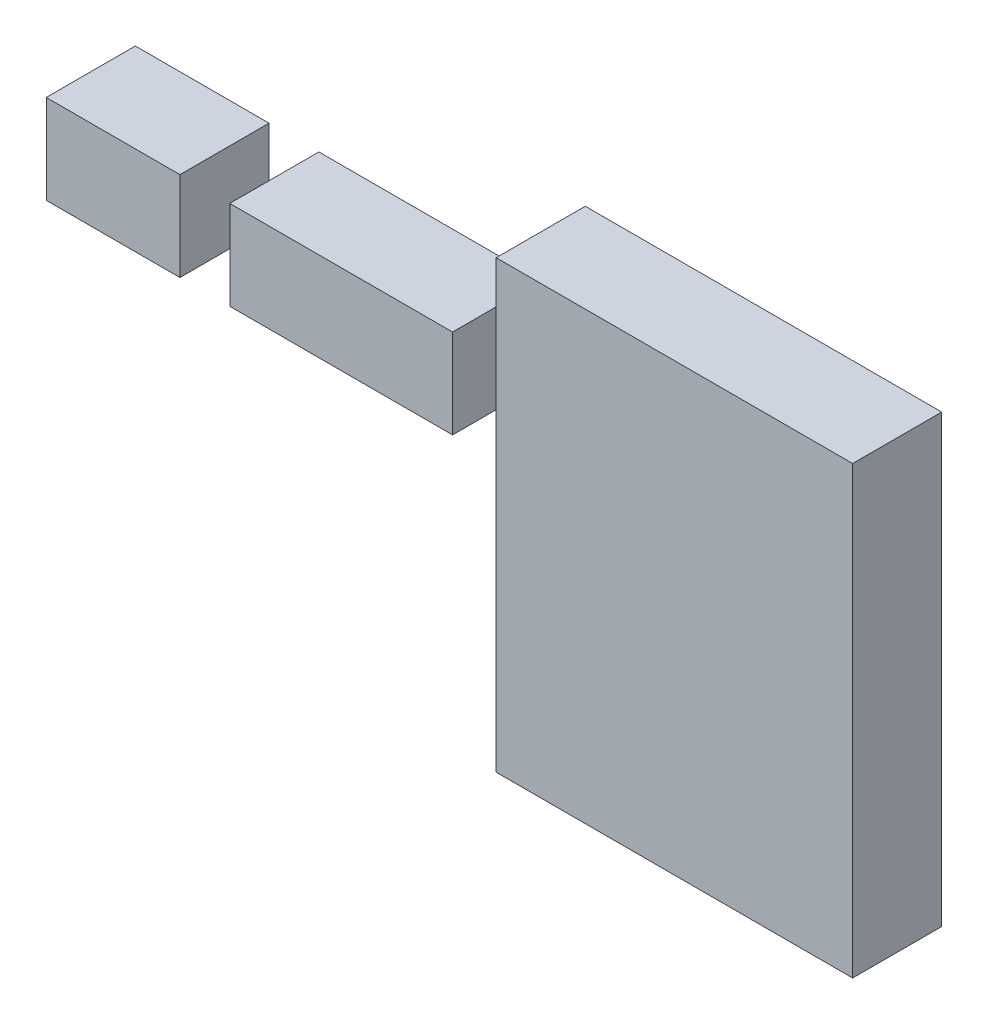
SolidWorks part; units mm, degrees
ref_plane "Front Plane" through (0, 0, 0) normal (0, 0, 1) x (1, 0, 0)
ref_plane "Top Plane" through (0, 0, 0) normal (0, 1, 0) x (1, 0, 0)
ref_plane "Right Plane" through (0, 0, 0) normal (1, 0, 0) x (0, 0, -1)
sketch "Sketch1" plane through (0, 0, 0) normal (0, 0, 1) x (1, 0, 0)
  line L1 (0, 0) -> (-8, 0)
  line L2 (0, 0) -> (0, 10)
  line L3 (0, 10) -> (-8, 10)
  line L4 (-8, 0) -> (-8, 10)
  line L5 (-13.9789, 8.0658) -> (-8.9789, 8.0658)
  line L6 (-13.9789, 8.0658) -> (-13.9789, 6.0658)
  line L7 (-13.9789, 6.0658) -> (-8.9789, 6.0658)
  line L8 (-8.9789, 8.0658) -> (-8.9789, 6.0658)
  line L9 (-18.0977, 8.0658) -> (-15.0977, 8.0658)
  line L10 (-18.0977, 8.0658) -> (-18.0977, 6.0658)
  line L11 (-18.0977, 6.0658) -> (-15.0977, 6.0658)
  line L12 (-15.0977, 8.0658) -> (-15.0977, 6.0658)
  point P13 (-15.0977, 6.0658)
  dimension "D1" = 10
  dimension "D2" = 8
  dimension "D3" = 2
  dimension "D4" = 5
  dimension "D5" = 3
  dimension "D6" = 2
extrude "Boss-Extrude1" add sketch "Sketch1" along normal blind 2
